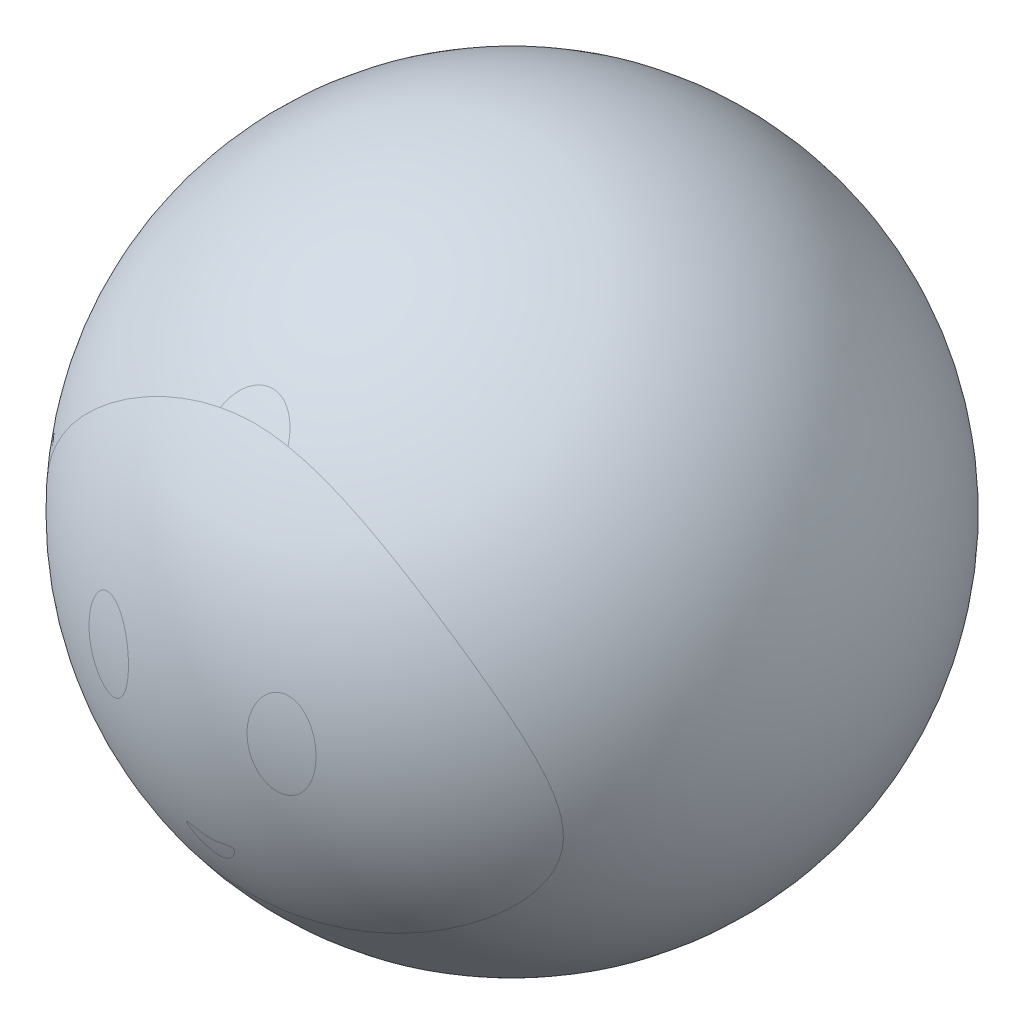
SolidWorks part; units mm, degrees
ref_plane "Front Plane" through (0, 0, 0) normal (0, 0, 1) x (1, 0, 0)
ref_plane "Top Plane" through (0, 0, 0) normal (0, 1, 0) x (1, 0, 0)
ref_plane "Right Plane" through (0, 0, 0) normal (1, 0, 0) x (0, 0, -1)
sketch "Sketch1" plane through (0, 0, 0) normal (1, 0, 0) x (0, 0, -1)
  line L0 (0, 43.7995) -> (0, -58.568) construction
  line L1 (0, 35) -> (0, -35)
  arc A0 (0, 35) -> (0, -35) centre (0, 0) ccw
  dimension "D1" = 70
revolve "Revolve1" add sketch "Sketch1" angle 360 about L0
sketch "Sketch2" plane through (0, 0, 0) normal (0, 0, 1) x (1, 0, 0)
  line L0 (0, 32.5665) -> (0, -37.487) construction
  spline S0 degree 3 poles (-0.1232, -26.5733) (-39.9816, -7.7449) (0.2868, 38.756) (40.8208, -8.744) (-0.1232, -26.5733) (-39.9816, -7.7449) (0.2868, 38.756) knots -0.722192 -0.437872 -0.219057 0 0.277808 0.562128 0.780943 1 1.277808 1.562128 1.780943 only from (-26.3525, -6.0825) to (-26.3525, -6.0825)
  point P5 (0, 0)
  point P7 (0, 0)
  point P9 (0, 0)
  point P10 (26.9825, -3.5627)
  point P11 (0, 0)
  point P12 (0, 0)
  point P13 (-26.3525, -6.0825)
  point P14 (26.7725, -6.9224)
  point P15 (0, 21.8449)
  point P16 (0, 0)
split line "Split Line3"
sketch "Sketch6" plane through (0, 0, 0) normal (0, 0, 1) x (1, 0, 0)
  circle A0 centre (0, 20.2776) radius 3.7855
  point P2 (0, 0)
  point P3 (0, 20.2776)
split line "Split Line4"
sketch "Sketch7" plane through (0, 0, 0) normal (0, 0, 1) x (1, 0, 0)
  line L0 (0, 11.2853) -> (0, -12.9039) construction
  ellipse E0 centre (-9.1721, 0) end of major axis (-9.1721, -4.631) minor radius 2.8775
  ellipse E1 centre (9.1721, 0) end of major axis (9.1721, 4.631) minor radius 2.8775
split line "Split Line5"
sketch "Sketch8" plane through (0, 0, 0) normal (0, 0, 1) x (1, 0, 0)
  spline S0 degree 3 poles (3.9113, -12.4561) (0.0699, -14.4945) (-3.5866, -12.4575) (-0.0003, -18.0282) (3.9113, -12.4561) (0.0699, -14.4945) (-3.5866, -12.4575) knots -0.799772 -0.513214 -0.217201 0 0.200228 0.486786 0.782799 1 1.200228 1.486786 1.782799 only from (0, -13.8931) to (0, -13.8931)
  point P2 (0, 0)
  point P4 (0, 0)
  point P6 (0, 0)
  point P7 (0, 0)
  point P8 (-0.5975, -15.7278)
  point P9 (2.4841, -13.8151)
  point P10 (-2.3331, -13.5317)
  point P11 (0, 0)
  point P12 (1.9174, -13.0004)
  point P13 (2.0945, -13.6734)
  point P14 (0, -15.9758)
  point P15 (2.5424, -13.5844)
  point P16 (0, 0)
split line "Split Line6"
sketch "Sketch9" plane through (0, 0, 0) normal (0, 1, 0) x (1, 0, 0)
  line L0 (0, -7.7783) -> (0, 12.814) construction
  circle A0 centre (0, 0) radius 2.5
  dimension "D1" = 5
extrude "Boss-Extrude2" add sketch "Sketch9" against normal blind 37
